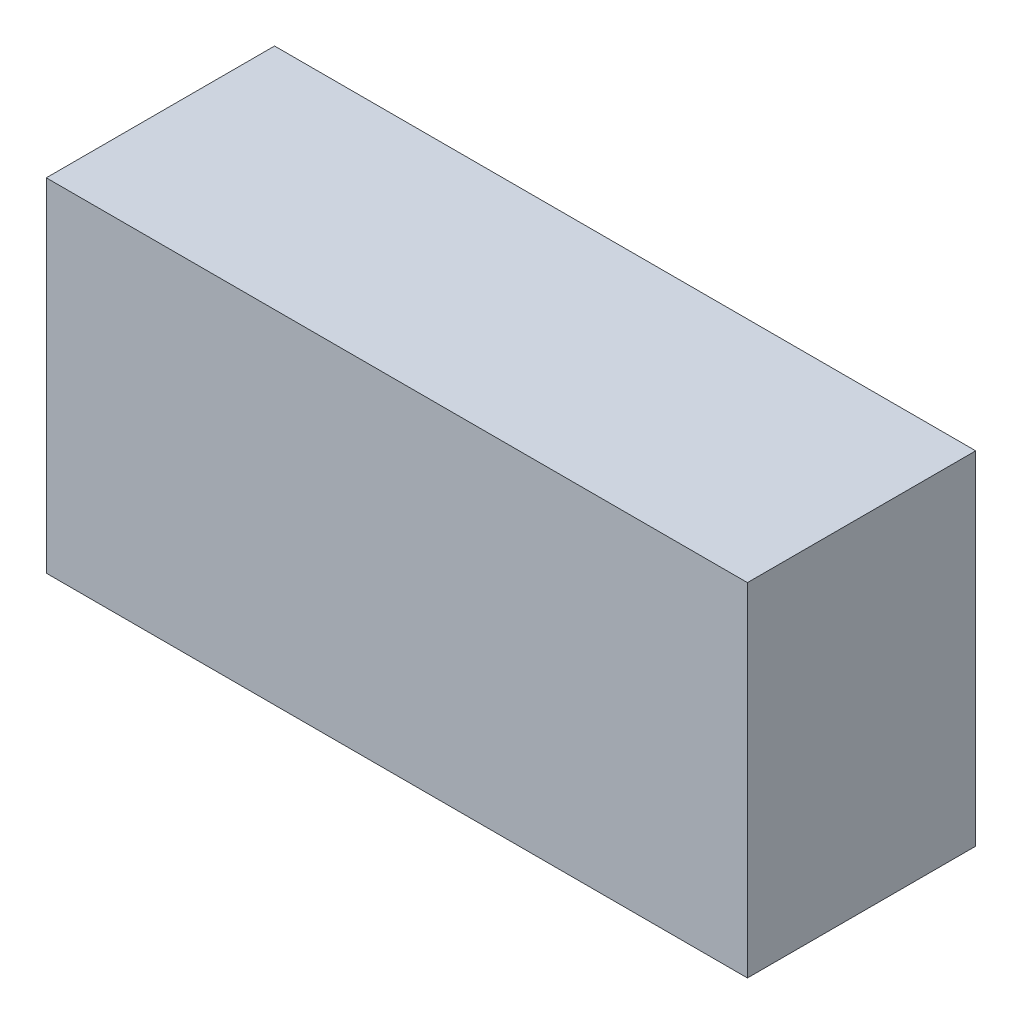
SolidWorks part; units mm, degrees
ref_plane "Alzado" through (0, 0, 0) normal (0, 0, 1) x (1, 0, 0)
ref_plane "Planta" through (0, 0, 0) normal (0, 1, 0) x (1, 0, 0)
ref_plane "Vista lateral" through (0, 0, 0) normal (1, 0, 0) x (0, 0, -1)
sketch "Croquis1" plane through (0, 0, 0) normal (0, 0, 1) x (1, 0, 0)
  line L1 (-21.5, 21) -> (21.5, 21)
  line L2 (-21.5, 21) -> (-21.5, 0)
  line L3 (-21.5, 0) -> (21.5, 0)
  line L4 (21.5, 21) -> (21.5, 0)
  dimension "D1" = 43
  dimension "D2" = 21
extrude "Saliente-Extruir1" add sketch "Croquis1" along normal blind 14
